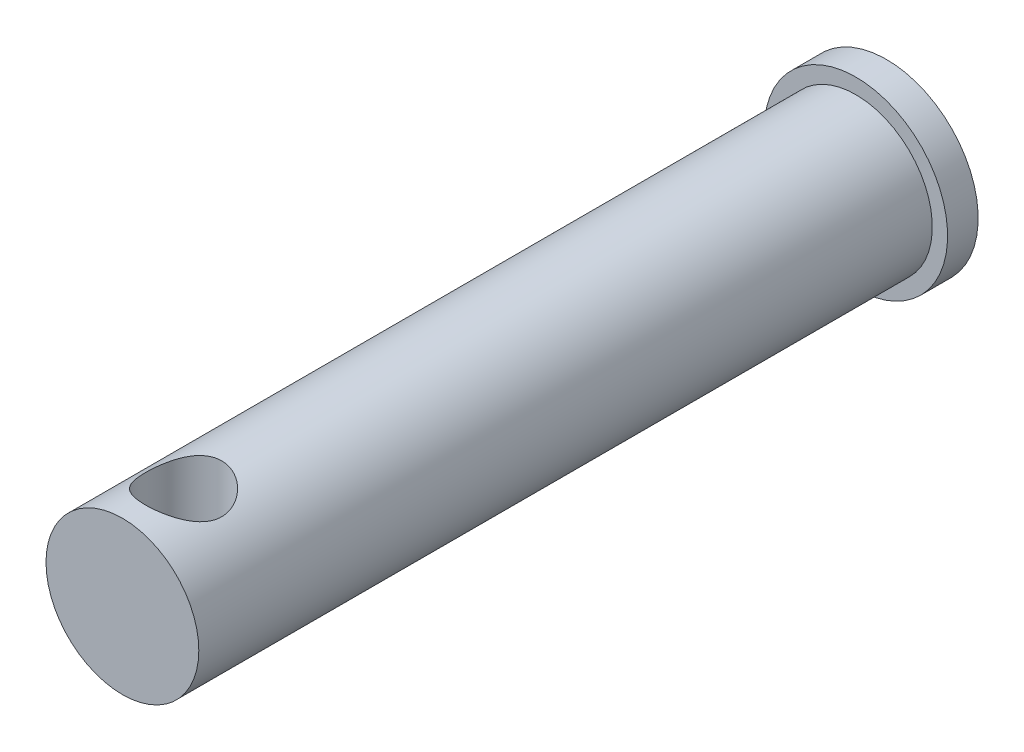
SolidWorks part; units mm, degrees
material "1023 Carbon Steel Sheet (SS)"
ref_plane "Front Plane" through (0, 0, 0) normal (0, 0, 1) x (1, 0, 0)
ref_plane "Top Plane" through (0, 0, 0) normal (0, 1, 0) x (1, 0, 0)
ref_plane "Right Plane" through (0, 0, 0) normal (1, 0, 0) x (0, 0, -1)
sketch "Sketch3" plane through (0, 0, 0) normal (0, 0, 1) x (1, 0, 0)
  circle A0 centre (0, 0) radius 0.635
  dimension "D1" = 1.27
extrude "Boss-Extrude1" add sketch "Sketch3" along normal mid plane 6.35
sketch "Sketch4" plane through (0, 0, 0) normal (0, 1, 0) x (1, 0, 0)
  line L0 (0, -3.175) -> (0, -2.667) construction
  line L1 (-0.635, -3.175) -> (0.635, -3.175) construction
  circle A0 centre (0, -2.667) radius 0.3175
  dimension "D1" = 0.635
  dimension "D2" = 0.508
extrude "Cut-Extrude1" cut sketch "Sketch4" against normal mid plane 3.048
sketch "Sketch5" plane through (0, 0, -3.175) normal (0, 0, -1) x (-1, 0, 0)
  circle A0 centre (0, 0) radius 0.762
  circle A1 centre (0, 0) radius 0.635
  circle A2 centre (0, 0) radius 0.635 construction
  dimension "D1" = 0.127
extrude "Boss-Extrude2" add sketch "Sketch5" against normal blind 0.254
